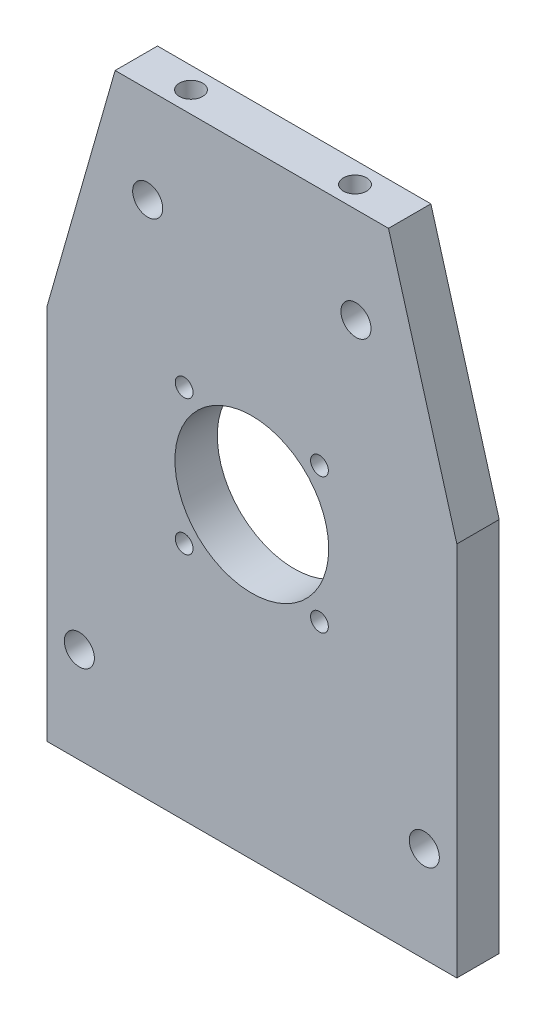
SolidWorks part; units mm, degrees
material "6061 Alloy"
ref_plane "Front Plane" through (0, 0, 0) normal (0, 0, 1) x (1, 0, 0)
ref_plane "Top Plane" through (0, 0, 0) normal (0, 1, 0) x (1, 0, 0)
ref_plane "Right Plane" through (0, 0, 0) normal (1, 0, 0) x (0, 0, -1)
sketch "Sketch1" plane through (0, 0, 0) normal (0, 0, 1) x (1, 0, 0)
  line L0 (-20, 45) -> (20, 45)
  line L5 (-30, -45) -> (30, -45)
  line L6 (0, 45) -> (0, -45) construction
  line L7 (-20, 45) -> (-30, 10)
  line L8 (-30, 10) -> (-30, -45)
  line L9 (30, 10) -> (30, -45)
  line L10 (20, 45) -> (30, 10)
  dimension "D1" = 90
  dimension "D2" = 60
  dimension "D3" = 40
  dimension "D4" = 55
extrude "1/4" add sketch "Sketch1" along normal mid plane 6.2
sketch "Sketch3" plane through (0, 0, 0) normal (0, 0, 1) x (1, 0, 0)
  circle A0 centre (0, 0) radius 11.25
  dimension "D1" = 22.5
extrude "Cut-Extrude2" cut sketch "Sketch3" along normal up to surface (3.1 mm away) and the other way blind 8 up to face at (0, 3.3333, 3.1)
sketch "Sketch2" plane through (0, 0, 3.1) normal (0, 0, 1) x (1, 0, 0)
  line L0 (-9.8995, 9.8995) -> (0, 0) construction
  line L1 (20, 45) -> (-20, 45) construction
  circle A0 centre (0, 0) radius 14 construction
  circle A1 centre (-9.8995, 9.8995) radius 1.3
  circle A2 centre (9.8995, 9.8995) radius 1.3
  circle A3 centre (9.8995, -9.8995) radius 1.3
  circle A4 centre (-9.8995, -9.8995) radius 1.3
  point P16 (0, 0)
  dimension "D1" = 28
  dimension "D3" = 2.6
  dimension "D2" = 45
  dimension "D4" = 4
extrude "M3_DRILL" cut sketch "Sketch2" against normal up to surface (6.2 mm away) up to face at (11.25, 0, -3.1)
sketch "Sketch4" plane through (0, 45, 0) normal (0, 1, 0) x (1, 0, 0)
  line L0 (0, -3.1) -> (0, 3.1) construction
  line L1 (0, 0) -> (-12, 0) construction
  line L2 (20, -3.1) -> (-20, -3.1) construction
  line L3 (20, 3.1) -> (-20, 3.1) construction
  circle A0 centre (-12, 0) radius 1.7
  circle A1 centre (12, 0) radius 1.7
  dimension "D2" = 3.4
  dimension "D1" = 12
extrude "M4_DRILL" cut sketch "Sketch4" against normal blind 8
sketch "Sketch5" plane through (0, -45, 0) normal (0, -1, 0) x (-1, 0, 0)
  line L0 (0, -3.1) -> (0, 3.1) construction
  line L2 (0, 0) -> (-20, 0) construction
  line L3 (30, -3.1) -> (-30, -3.1) construction
  line L4 (30, 3.1) -> (-30, 3.1) construction
  circle A0 centre (-20, 0) radius 1.7
  circle A1 centre (20, 0) radius 1.7
  circle A2 centre (0, 0) radius 1.7
  dimension "D1" = 3.4
  dimension "D2" = 20
extrude "M4_DRILL2" cut sketch "Sketch5" against normal blind 8
sketch "Sketch6" plane through (0, 0, 3.1) normal (0, 0, 1) x (1, 0, 0)
  line L2 (0, 0) -> (0, -45.222) construction
  line L4 (20, 45) -> (-20, 45) construction
  line L5 (-30, -45) -> (30, -45) construction
  line L6 (-30, 10) -> (-30, -45) construction
  circle A0 centre (-25.2375, -31) radius 2.2
  circle A1 centre (25.2375, -31) radius 2.2
  circle A2 centre (-15.2375, 31) radius 2.2
  circle A3 centre (15.2375, 31) radius 2.2
  dimension "D1" = 4.4
  dimension "D6" = 4.4
  dimension "D2" = 14
  dimension "D3" = 4.7625
  dimension "D4" = 14
  dimension "D5" = 4.7625
extrude "M4_through" cut sketch "Sketch6" against normal up to surface (6.2 mm away) up to face at (-8.5995, -9.8995, -3.1)
